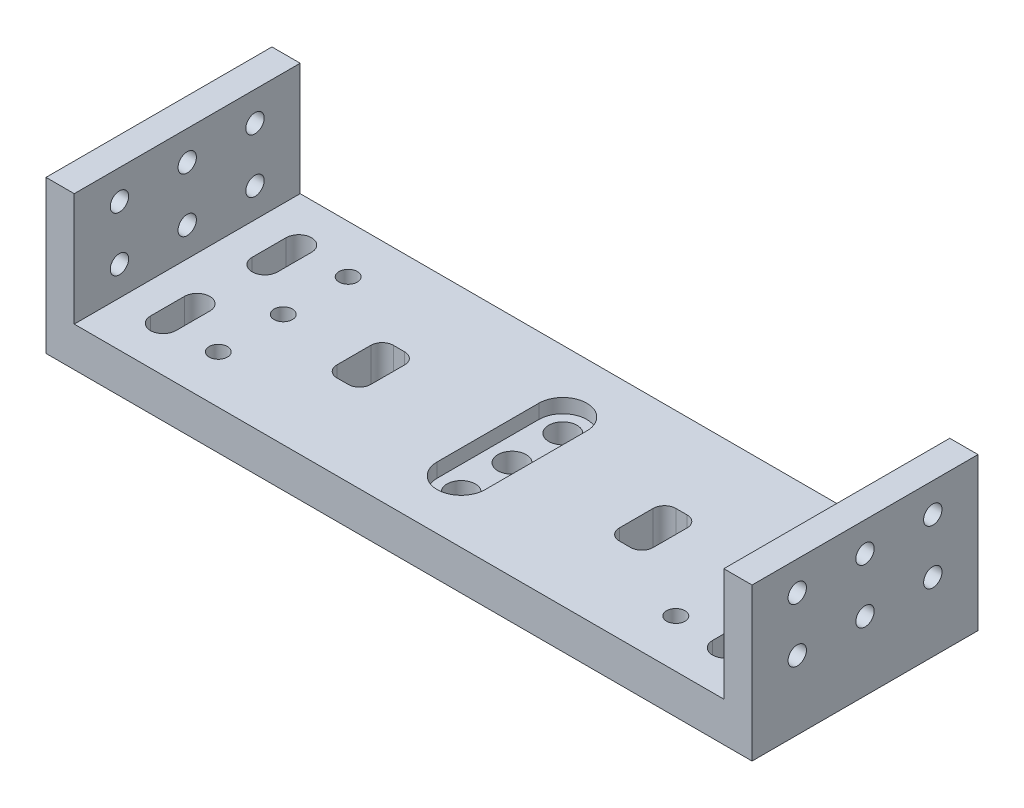
SolidWorks part; units mm, degrees
ref_plane "Plano frontal" through (0, 0, 0) normal (0, 0, 1) x (1, 0, 0)
ref_plane "Plano superior" through (0, 0, 0) normal (0, 1, 0) x (1, 0, 0)
ref_plane "Plano direito" through (0, 0, 0) normal (1, 0, 0) x (0, 0, -1)
sketch "Esboço1" plane through (0, 0, 0) normal (0, 1, 0) x (1, 0, 0)
  line L1 (62.5, -20) -> (-62.5, -20)
  line L2 (62.5, -20) -> (62.5, 20)
  line L3 (62.5, 20) -> (-62.5, 20)
  line L4 (-62.5, -20) -> (-62.5, 20)
  line L5 (62.5, -20) -> (-62.5, 20) construction
  line L6 (62.5, 20) -> (-62.5, -20) construction
  point P0 (0, 0)
  dimension "D1" = 125
  dimension "D2" = 40
extrude "base" add sketch "Esboço1" along normal blind 7
sketch "Esboço2" plane through (0, 7, 0) normal (0, 1, 0) x (1, 0, 0)
  line L0 (-62.5, -20) -> (62.5, -20) construction
  line L1 (62.5, 20) -> (57.5, 20)
  line L2 (62.5, 20) -> (62.5, -20)
  line L3 (62.5, -20) -> (57.5, -20)
  line L4 (57.5, 20) -> (57.5, -20)
  line L6 (-62.5, 20) -> (-57.5, 20)
  line L7 (-62.5, 20) -> (-62.5, -20)
  line L8 (-62.5, -20) -> (-57.5, -20)
  line L9 (-57.5, 20) -> (-57.5, -20)
  dimension "D1" = 5
extrude "suporte lateral" add sketch "Esboço2" along normal blind 20
sketch "Esboço3" plane through (0, 7, 0) normal (0, 1, 0) x (1, 0, 0)
  line L0 (0, 20) -> (0, -20) construction
  line L1 (57.5, 20) -> (-57.5, 20) construction
  line L2 (-57.5, -20) -> (57.5, -20) construction
  line L3 (-40.5, 20) -> (-40.5, -20) construction
  line L4 (0, 0) -> (-40.5, 0) construction
  line L5 (-40.5, 11.5) -> (0, 11.5) construction
  line L6 (-40.5, -11.5) -> (0, -11.5) construction
  line L8 (-20.25, 11.5) -> (-20.25, 0) construction
  line L9 (-20.25, 0) -> (-20.25, -11.5) construction
  circle A0 centre (-40.5, 0) radius 1.625
  circle A2 centre (-40.5, 11.5) radius 1.625
  circle A3 centre (-40.5, -11.5) radius 1.625
  circle A4 centre (40.5, 11.5) radius 1.625
  circle A5 centre (40.5, 0) radius 1.625
  circle A6 centre (40.5, -11.5) radius 1.625
  dimension "D2" = 3.25
  dimension "D1" = 40.5
  dimension "D3" = 11.5
extrude "furo motor" cut sketch "Esboço3" against normal up to surface (7 mm away) up to face at (0, 0, 0)
sketch "Esboço4" plane through (0, 7, 0) normal (0, 1, 0) x (1, 0, 0)
  line L0 (0, 20) -> (0, -20) construction
  line L1 (57.5, 20) -> (-57.5, 20) construction
  line L2 (-57.5, -20) -> (57.5, -20) construction
  line L3 (22, 5) -> (28, 5)
  line L4 (0, 0) -> (-25, 0) construction
  line L9 (28, -5) -> (28, 5)
  line L10 (22, -5) -> (28, -5)
  line L11 (-22, -5) -> (-28, -5)
  line L12 (-22, -5) -> (-22, 5)
  line L13 (-22, 5) -> (-28, 5)
  line L14 (-28, -5) -> (-28, 5)
  line L15 (-22, -5) -> (-28, 5) construction
  line L16 (-22, 5) -> (-28, -5) construction
  line L17 (22, -5) -> (22, 5)
  point P13 (-25, 0)
  dimension "D1" = 25
  dimension "D2" = 6
  dimension "D3" = 10
extrude "Corte-extrusão2" cut sketch "Esboço4" against normal through all
sketch "Esboço5" plane through (0, 7, 0) normal (0, 1, 0) x (1, 0, 0)
  line L0 (0, 20) -> (0, 9) construction
  line L3 (57.5, 20) -> (-57.5, 20) construction
  line L5 (0, -9) -> (0, -20) construction
  line L6 (-57.5, -20) -> (57.5, -20) construction
  circle A0 centre (0, 9) radius 2.5
  circle A1 centre (0, -9) radius 2.5
  dimension "D2" = 5
  dimension "D1" = 11
extrude "Corte-extrusão3" cut sketch "Esboço5" against normal through all both and the other way through all
sketch "Esboço7" plane through (0, 7, 0) normal (0, 1, 0) x (1, 0, 0)
  line L0 (-57.5, -20) -> (57.5, -20) construction
  line L1 (-57.5, 20) -> (-52, 20)
  line L2 (-57.5, 20) -> (-57.5, -20)
  line L3 (-57.5, -20) -> (-52, -20)
  line L4 (-52, 20) -> (-52, -20)
  line L5 (-40.5, 11.5) -> (-40.5, -20) construction
  line L6 (-47.5, 20) -> (-47.5, -20)
  line L7 (57.5, 20) -> (-57.5, 20) construction
  line L8 (-52, 20) -> (-47.5, 20) construction
  line L9 (-49.75, 20) -> (-49.75, -20) construction
  line L10 (-49.75, 12) -> (-49.75, 6) construction
  line L11 (-47.5, 12) -> (-47.5, 6)
  line L12 (-52, 12) -> (-52, 6)
  line L13 (-49.75, -12) -> (-49.75, -6) construction
  line L14 (-52, -12) -> (-52, -6)
  line L15 (-47.5, -12) -> (-47.5, -6)
  line L16 (0, 0) -> (-49.75, 0) construction
  line L17 (0, 20) -> (0, 0) construction
  line L18 (0, 0) -> (0, -20) construction
  line L19 (49.75, -12) -> (49.75, -6) construction
  line L20 (52, -12) -> (52, -6)
  line L21 (47.5, -12) -> (47.5, -6)
  line L22 (49.75, 12) -> (49.75, 6) construction
  line L23 (47.5, 12) -> (47.5, 6)
  line L24 (52, 12) -> (52, 6)
  arc A0 (-47.5, 12) -> (-52, 12) centre (-49.75, 12) ccw
  arc A1 (-52, 6) -> (-47.5, 6) centre (-49.75, 6) ccw
  arc A2 (-52, -12) -> (-47.5, -12) centre (-49.75, -12) ccw
  arc A3 (-47.5, -6) -> (-52, -6) centre (-49.75, -6) ccw
  arc A4 (52, -12) -> (47.5, -12) centre (49.75, -12) cw
  arc A5 (47.5, -6) -> (52, -6) centre (49.75, -6) cw
  arc A6 (47.5, 12) -> (52, 12) centre (49.75, 12) cw
  arc A7 (52, 6) -> (47.5, 6) centre (49.75, 6) cw
  point P16 (-49.75, 9)
  point P23 (-49.75, -9)
  point P37 (49.75, -9)
  point P44 (49.75, 9)
  dimension "D1" = 5.5
  dimension "D2" = 7
  dimension "D3" = 8
  dimension "D4" = 8
  dimension "D5" = 6
  dimension "D6" = 6
extrude "Corte-extrusão4" cut sketch "Esboço7" against normal through all contours A7 L24 A6 L23 | A5 L21 A4 L20 | L6 A3 L4 A2 | L4 A1 L6 A0
sketch "Esboço8" plane through (0, 7, 0) normal (0, 1, 0) x (1, 0, 0)
  line L0 (0, 9) -> (0, -9) construction
  line L1 (4.25, 9) -> (4.25, -9)
  line L2 (-4.25, 9) -> (-4.25, -9)
  arc A0 (4.25, 9) -> (-4.25, 9) centre (0, 9) ccw
  arc A1 (-4.25, -9) -> (4.25, -9) centre (0, -9) ccw
  point P4 (0, 0)
  dimension "D1" = 4.25
extrude "Corte-extrusão5" cut sketch "Esboço8" against normal blind 2.5
sketch "Esboço9" plane through (0, 4.5, 0) normal (0, 1, 0) x (1, 0, 0)
  circle A0 centre (0, 0) radius 2.5
  dimension "D1" = 5
extrude "Corte-extrusão6" cut sketch "Esboço9" against normal through all contours A0
sketch "Esboço10" plane through (57.5, 0, 0) normal (-1, 0, 0) x (0, 0, 1)
  circle A0 centre (-12, 12.2) radius 1.6 construction
  circle A1 centre (-12, 21.8) radius 1.6 construction
  circle A2 centre (0, 21.8) radius 1.6 construction
  circle A3 centre (0, 12.2) radius 1.6 construction
  circle A4 centre (12, 12.2) radius 1.6 construction
  circle A5 centre (12, 21.8) radius 1.6 construction
  circle A6 centre (-12, 12.2) radius 1.6 construction
  circle A7 centre (-12, 21.8) radius 1.6 construction
  circle A8 centre (0, 21.8) radius 1.6 construction
  circle A9 centre (0, 12.2) radius 1.6 construction
  circle A10 centre (12, 12.2) radius 1.6 construction
  circle A11 centre (12, 21.8) radius 1.6 construction
  circle A12 centre (-12, 21.8) radius 1.625
  circle A13 centre (0, 21.8) radius 1.625
  circle A14 centre (12, 21.8) radius 1.625
  circle A15 centre (-12, 12.2) radius 1.625
  circle A16 centre (0, 12.2) radius 1.625
  circle A17 centre (12, 12.2) radius 1.625
  dimension "D1" = 3.25
extrude "Corte-extrusão7" cut sketch "Esboço10" against normal through all both and the other way through all
fillet "Filete1" radius 2 8 edges at (-22, 3.5, -5) (-28, 3.5, -5) (-22, 3.5, 5) (-28, 3.5, 5) (22, 3.5, -5) (22, 3.5, 5) (28, 3.5, -5) (28, 3.5, 5)
equation "\"3d\"= 0.25mm"
equation "\"D1@Esboço10\"=3.00mm + \"3d\""
equation "\"D2@Esboço3\"=3.00mm + \"3d\""
